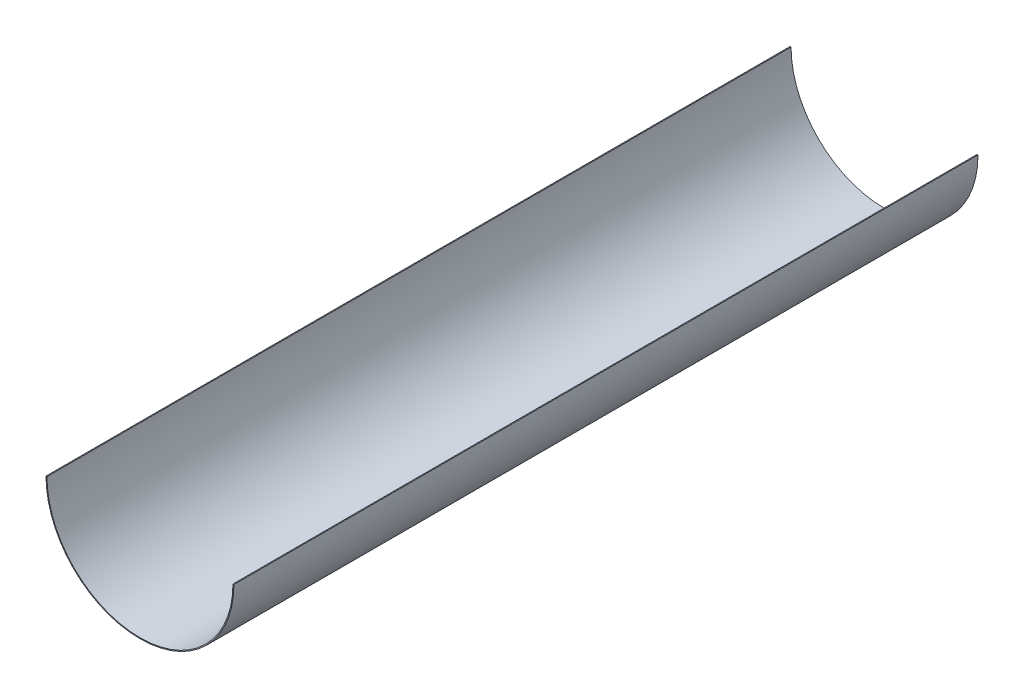
SolidWorks part; units mm, degrees
ref_plane "Front" through (0, 0, 0) normal (0, 0, 1) x (1, 0, 0)
ref_plane "Top" through (0, 0, 0) normal (0, 1, 0) x (1, 0, 0)
ref_plane "Right" through (0, 0, 0) normal (1, 0, 0) x (0, 0, -1)
sketch "Эскиз2" plane through (0, 0, 0) normal (0, 0, 1) x (1, 0, 0)
  line L0 (-1010, 0) -> (-1000, 0)
  line L1 (1000, 0) -> (1010, 0)
  arc A0 (-1000, 0) -> (1000, 0) centre (0, 0) ccw
  arc A1 (-1010, 0) -> (1010, 0) centre (0, 0) ccw
extrude "Бобышка-Вытянуть1" add sketch "Эскиз2" along normal blind 8000
